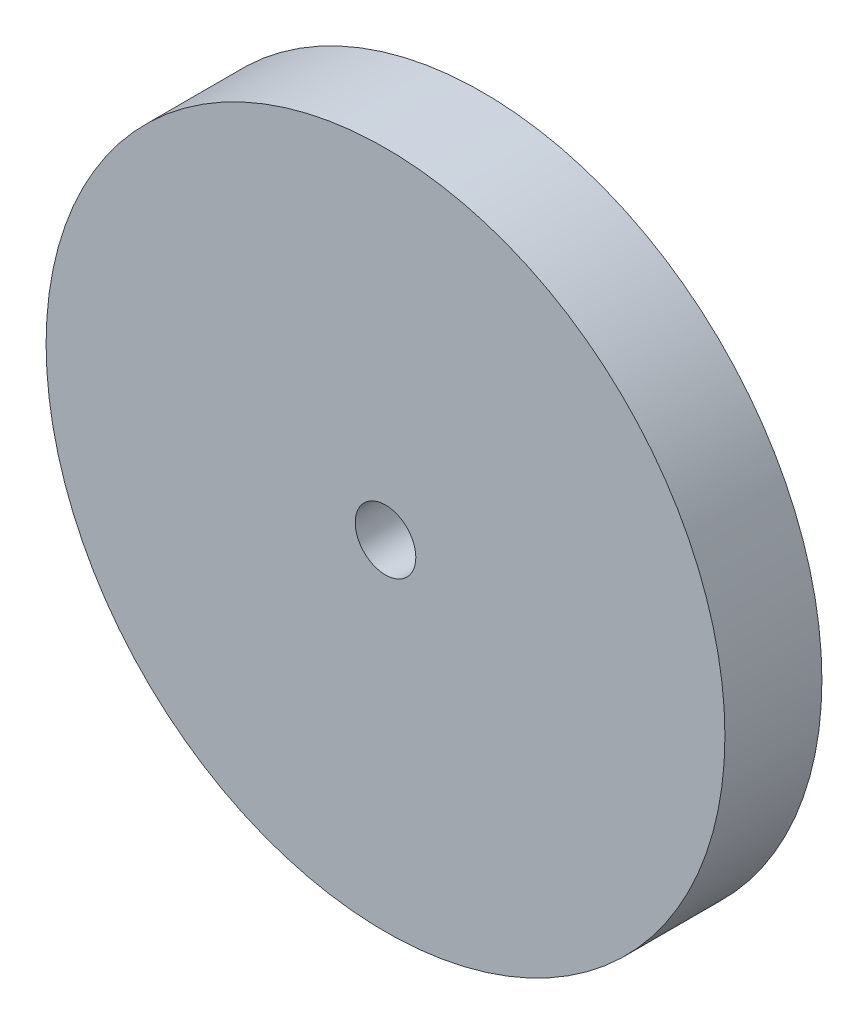
SolidWorks part; units mm, degrees
ref_plane "前视基准面" through (0, 0, 0) normal (0, 0, 1) x (1, 0, 0)
ref_plane "上视基准面" through (0, 0, 0) normal (0, 1, 0) x (1, 0, 0)
ref_plane "右视基准面" through (0, 0, 0) normal (1, 0, 0) x (0, 0, -1)
other "Configuration Table"
sketch "草图1" plane through (0, 0, 0) normal (0, 0, 1) x (1, 0, 0)
  circle A0 centre (0, 0) radius 140
  circle A1 centre (0, 0) radius 12.5
extrude "凸台-拉伸1" add sketch "草图1" along normal blind 40
